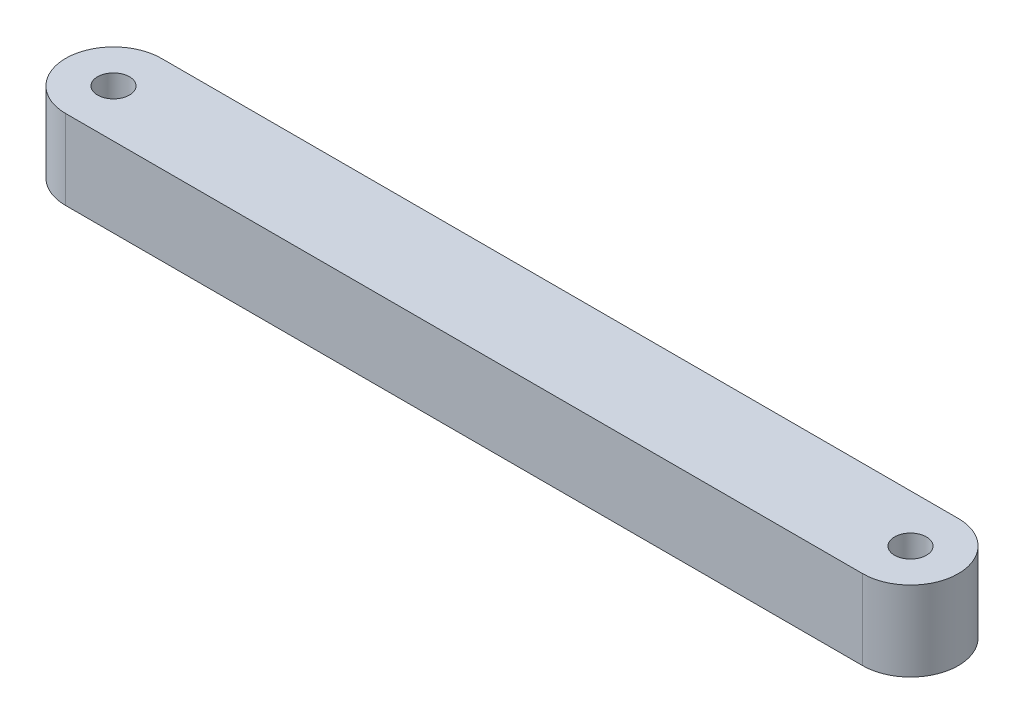
SolidWorks part; units mm, degrees
ref_plane "Front Plane" through (0, 0, 0) normal (0, 0, 1) x (1, 0, 0)
ref_plane "Top Plane" through (0, 0, 0) normal (0, 1, 0) x (1, 0, 0)
ref_plane "Right Plane" through (0, 0, 0) normal (1, 0, 0) x (0, 0, -1)
sketch "Sketch3" plane through (0, 0, 0) normal (0, 1, 0) x (1, 0, 0)
  line L0 (-63.5, 0) -> (63.5, 0) construction
  line L1 (-6.985, 0) -> (6.985, 0) construction
  line L2 (-63.5, 7.62) -> (63.5, 7.62)
  line L3 (-63.5, -7.62) -> (63.5, -7.62)
  arc A0 (-63.5, 7.62) -> (-63.5, -7.62) centre (-63.5, 0) ccw
  arc A1 (63.5, -7.62) -> (63.5, 7.62) centre (63.5, 0) ccw
  point P5 (0, 0)
  dimension "D2" = 7.62
  dimension "D1" = 127
  dimension "D3" = 63.5
extrude "Boss-Extrude1" add sketch "Sketch3" along normal blind 12.7
sketch "Sketch4" plane through (0, 12.7, 0) normal (0, 1, 0) x (1, 0, 0)
  line L0 (0, -6.985) -> (0, 6.985) construction
  circle A0 centre (-63.5, 0) radius 2.54
  circle A1 centre (63.5, 0) radius 2.54
  dimension "D1" = 5.08
extrude "Cut-Extrude3" cut sketch "Sketch4" against normal through all
equation "\"TibiaLength\"= 5in"
equation "\"TibiaRadius\"= 0.3in"
equation "\"TibiaDistFromCentre\"= \"TibiaLength\" / 2"
equation "\"TibiaThickness\"= 0.5in"
equation "\"HoleRadius\"= 0.2in"
equation "\"D1@Sketch3\"= \"TibiaLength\""
equation "\"D2@Sketch3\"= \"TibiaRadius\""
equation "\"D3@Sketch3\"= \"TibiaDistFromCentre\""
equation "\"D1@Boss-Extrude1\"= \"TibiaThickness\""
equation "\"D1@Sketch4\"= \"HoleRadius\""
